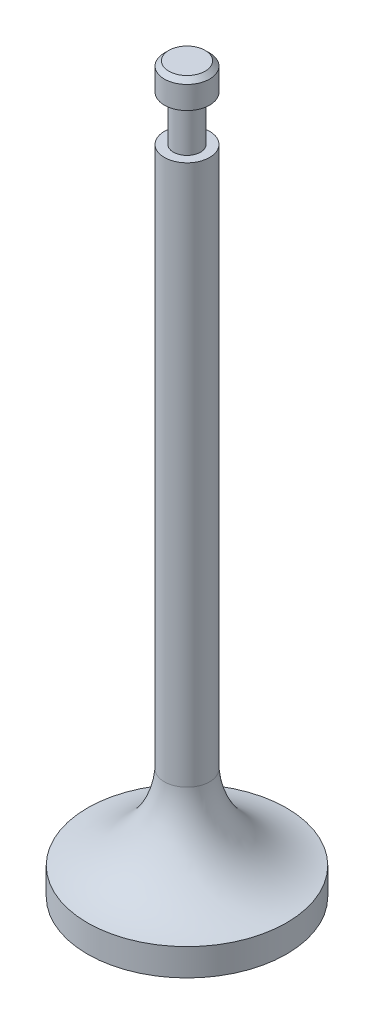
SolidWorks part; units mm, degrees
ref_plane "Front Plane" through (0, 0, 0) normal (0, 0, 1) x (1, 0, 0)
ref_plane "Top Plane" through (0, 0, 0) normal (0, 1, 0) x (1, 0, 0)
ref_plane "Right Plane" through (0, 0, 0) normal (1, 0, 0) x (0, 0, -1)
sketch "Sketch1" plane through (0, 0, 0) normal (0, 0, 1) x (1, 0, 0)
  line L0 (0, 0) -> (11, 0)
  line L1 (11, 0) -> (11, 3)
  line L2 (2.5, 12.2447) -> (2.5, 72)
  line L3 (2.5, 72) -> (1.5, 72)
  line L4 (1.5, 72) -> (1.5, 77)
  line L5 (1.5, 77) -> (2.5, 77)
  line L6 (2.5, 77) -> (2.5, 80)
  line L7 (2.5, 80) -> (0, 80)
  line L8 (0, 80) -> (0, -21.9886) construction
  line L9 (0, 80) -> (0, 0)
  arc A0 (11, 3) -> (2.5, 12.2447) centre (12.4792, 12.89) cw
  dimension "D1" = 11
  dimension "D3" = 10
  dimension "D6" = 5
  dimension "D2" = 3
  dimension "D4" = 2.5
  dimension "D5" = 12.89
  dimension "D7" = 2.5
  dimension "D8" = 3
  dimension "D9" = 80
  dimension "D10" = 1.5
revolve "Revolve1" add sketch "Sketch1" angle 360 about L9
chamfer "Chamfer1" distance 0.5 angle 45 1 edges at (-2.5, 80, 0)
